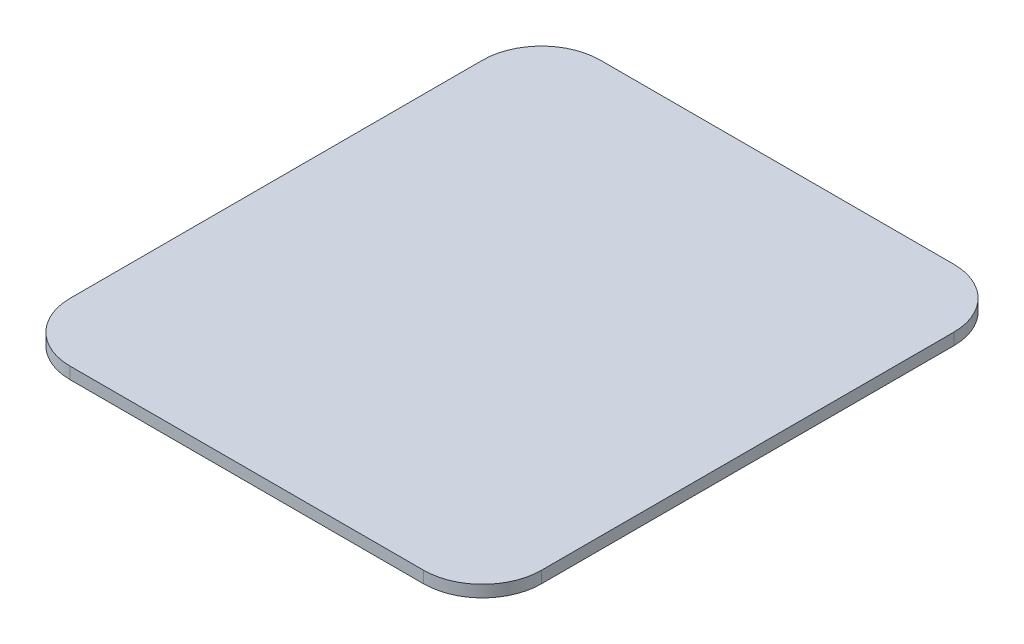
SolidWorks part; units mm, degrees
ref_plane "Front Plane" through (0, 0, 0) normal (0, 0, 1) x (1, 0, 0)
ref_plane "Top Plane" through (0, 0, 0) normal (0, 1, 0) x (1, 0, 0)
ref_plane "Right Plane" through (0, 0, 0) normal (1, 0, 0) x (0, 0, -1)
sketch "Sketch1" plane through (0, 0, 0) normal (0, 1, 0) x (1, 0, 0)
  line L1 (-150, -225) -> (150, -225)
  line L2 (-200, -175) -> (-200, 175)
  line L3 (-150, 225) -> (150, 225)
  line L4 (200, -175) -> (200, 175)
  line L5 (-200, -225) -> (200, 225) construction
  line L6 (-200, 225) -> (200, -225) construction
  arc A0 (-150, -225) -> (-200, -175) centre (-150, -175) cw
  arc A1 (150, -225) -> (200, -175) centre (150, -175) ccw
  arc A2 (150, 225) -> (200, 175) centre (150, 175) cw
  arc A3 (-200, 175) -> (-150, 225) centre (-150, 175) cw
  point P0 (0, 0)
  dimension "D3" = 50
  dimension "D1" = 450
  dimension "D2" = 400
extrude "Boss-Extrude1" add sketch "Sketch1" along normal blind 10
